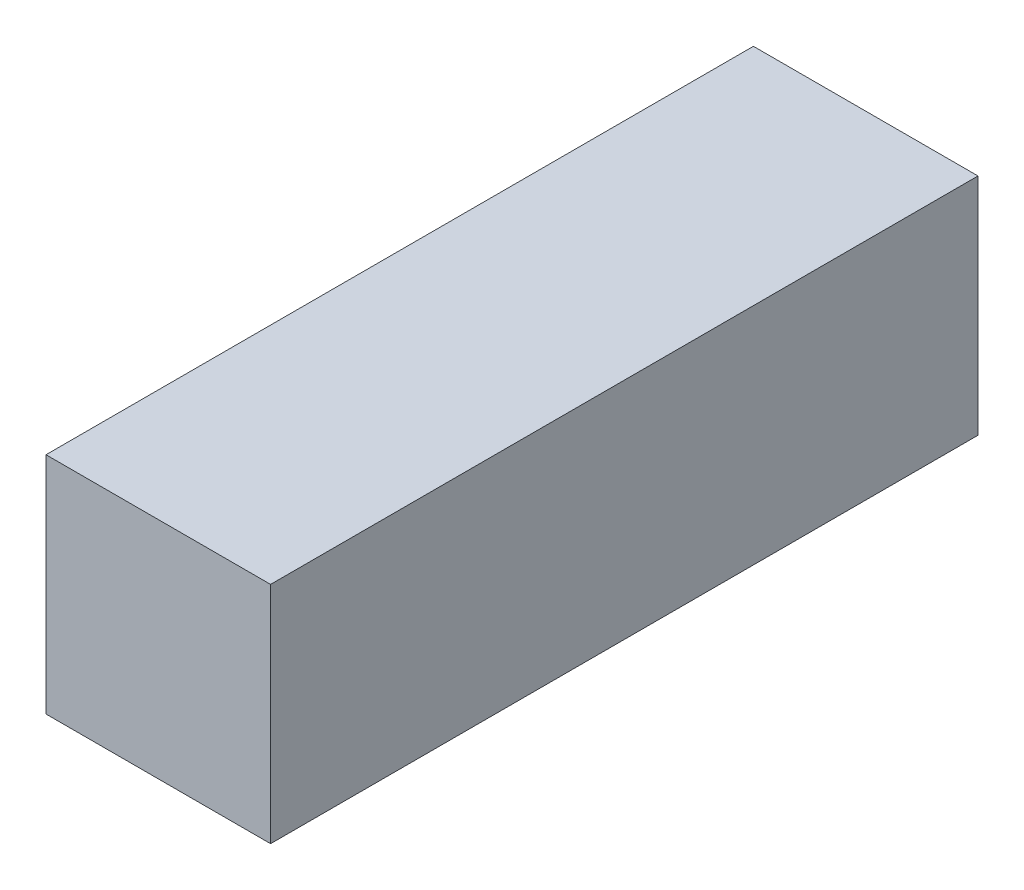
SolidWorks part; units mm, degrees
ref_plane "前视基准面" through (0, 0, 0) normal (0, 0, 1) x (1, 0, 0)
ref_plane "上视基准面" through (0, 0, 0) normal (0, 1, 0) x (1, 0, 0)
ref_plane "右视基准面" through (0, 0, 0) normal (1, 0, 0) x (0, 0, -1)
sketch "草图1" plane through (0, 0, 0) normal (0, 0, 1) x (1, 0, 0)
  line L1 (0, 0) -> (10.16, 0)
  line L2 (0, 0) -> (0, 10.16)
  line L3 (0, 10.16) -> (10.16, 10.16)
  line L4 (10.16, 0) -> (10.16, 10.16)
extrude "凸台-拉伸1" add sketch "草图1" along normal blind 32.004
